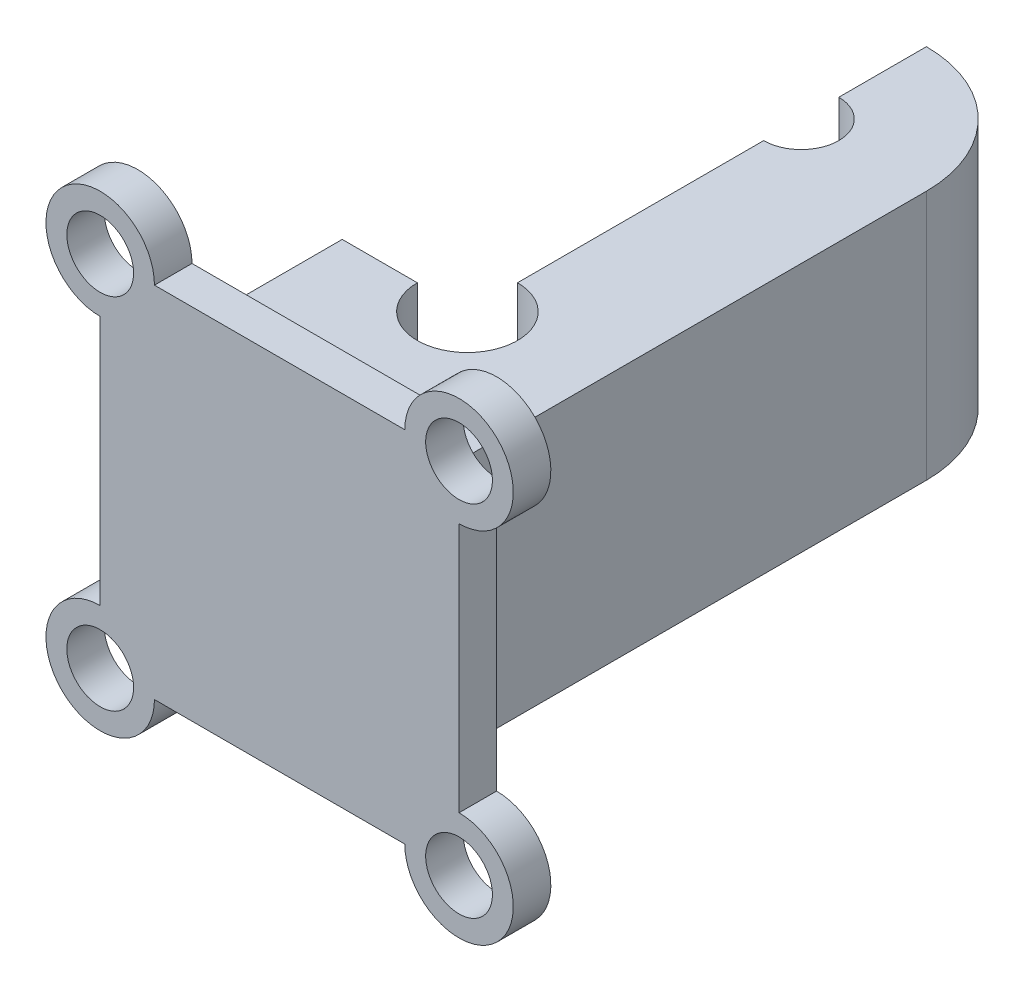
SolidWorks part; units mm, degrees
ref_plane "Ön Düzlem" through (0, 0, 0) normal (0, 0, 1) x (1, 0, 0)
ref_plane "Üst Düzlem" through (0, 0, 0) normal (0, 1, 0) x (1, 0, 0)
ref_plane "Sağ Düzlem" through (0, 0, 0) normal (1, 0, 0) x (0, 0, -1)
sketch "Çizim1" plane through (0, 0, 0) normal (0, 0, 1) x (1, 0, 0)
  line L5 (27.3051, -33.7264) -> (87.3051, -33.7264)
  line L10 (14.3051, -20.7264) -> (14.3051, 39.2736)
  line L12 (100.3051, 39.2736) -> (100.3051, -20.7264)
  line L13 (87.3051, 52.2736) -> (27.3051, 52.2736)
  circle A8 centre (14.3051, -33.7264) radius 13
  circle A10 centre (14.3051, -33.7264) radius 8
  circle A11 centre (100.3051, -33.7264) radius 8
  circle A12 centre (100.3051, -33.7264) radius 13
  circle A13 centre (14.3051, 52.2736) radius 8
  circle A14 centre (14.3051, 52.2736) radius 13
  circle A15 centre (100.3051, 52.2736) radius 8
  circle A16 centre (100.3051, 52.2736) radius 13
  dimension "D1" = 26
  dimension "D2" = 16
extrude "Yükseklik-Ekstrüzyon2" add sketch "Çizim1" along normal blind 9 contours A8 A10 | L12 A16 L13 A14 L10 A8 L5 A12 | A12 A11 | A16 A15 | A14 A13
sketch "Çizim2" plane through (0, 0, 0) normal (0, 0, -1) x (-1, 0, 0)
  line L0 (-57.3051, -33.7264) -> (-57.3051, 52.2736) construction
  line L1 (-27.3051, -33.7264) -> (-87.3051, -33.7264) construction
  line L2 (-87.3051, 52.2736) -> (-27.3051, 52.2736) construction
  line L4 (-87.3051, 39.2736) -> (-27.3051, 39.2736)
  line L5 (-87.3051, 39.2736) -> (-87.3051, -20.7264)
  line L6 (-87.3051, -20.7264) -> (-27.3051, -20.7264)
  line L7 (-27.3051, 39.2736) -> (-27.3051, -20.7264)
  line L8 (-87.3051, 39.2736) -> (-27.3051, -20.7264) construction
  line L9 (-87.3051, -20.7264) -> (-27.3051, 39.2736) construction
  point P6 (-57.3051, 9.2736)
  dimension "D1" = 60
  dimension "D2" = 60
extrude "Yükseklik-Ekstrüzyon3" add sketch "Çizim2" along normal blind 116
sketch "Çizim3" plane through (0, -20.7264, 0) normal (0, -1, 0) x (1, 0, 0)
  line L0 (57.3051, 0) -> (57.3051, -36) construction
  line L1 (27.3051, 0) -> (87.3051, 0) construction
  line L2 (57.3051, -48) -> (57.3051, -116)
  line L3 (87.3051, -116) -> (27.3051, -116) construction
  circle A0 centre (57.3051, -36) radius 12
  circle A1 centre (57.3051, -116) radius 30
  circle A2 centre (57.3051, -116) radius 10
  line M4 (27.3051, -116) -> (87.3051, -116)
  dimension "D2" = 24
  dimension "D3" = 60
  dimension "D4" = 20
  dimension "D1" = 36
extrude "Yükseklik-Ekstrüzyon4" add sketch "Çizim3" against normal blind 60 contours A2 A1 M4
sketch "Çizim4" plane through (0, -20.7264, 0) normal (0, -1, 0) x (1, 0, 0)
  line L1 (67.3051, -116) -> (47.3051, -116) construction
  circle A1 centre (57.3051, -116) radius 20
  dimension "D1" = 40
extrude "Kes-Ekstrüzyon2" cut sketch "Çizim4" against normal blind 220
sketch "Çizim5" plane through (0, -20.7264, 0) normal (0, -1, 0) x (1, 0, 0)
  line L0 (57.3051, 0) -> (57.3051, -36) construction
  line L1 (87.3051, 0) -> (27.3051, 0) construction
  circle A0 centre (57.3051, -36) radius 12
  dimension "D2" = 24
  dimension "D1" = 36
extrude "Kes-Ekstrüzyon3" cut sketch "Çizim5" against normal blind 220
sketch "Çizim6" plane through (0, -20.7264, 0) normal (0, -1, 0) x (-1, 0, 0)
  line L0 (-57.3051, 146) -> (-57.3051, 36)
  line L1 (-57.3051, 36) -> (-27.3051, 36)
  line L2 (-27.3051, 116) -> (-27.3051, 0) construction
  line L3 (-27.3051, 36) -> (-27.3051, 116)
  arc A0 (-27.3051, 116) -> (-87.3051, 116) centre (-57.3051, 116) ccw construction
  arc A1 (-57.3051, 146) -> (-27.3051, 116) centre (-57.3051, 116) cw
  circle M1 centre (-57.3051, 36) radius 12
  circle M2 centre (-57.3051, 116) radius 20
  line M4 (-27.3051, 0) -> (-27.3051, 116)
  arc M5 (-27.3051, 116) -> (-87.3051, 116) centre (-57.3051, 116) ccw
extrude "Kes-Ekstrüzyon4" cut sketch "Çizim6" against normal blind 220 contours L1 L0 M1 M4 M5 M2
ref_plane "Düzlem1" through (0, -0.7264, 0) normal (0, -1, 0) x (-1, 0, 0)
sketch "Çizim7" plane through (0, -0.7264, 0) normal (0, -1, 0) x (-1, 0, 0)
  line L0 (-57.3051, 131.1753) -> (-57.3051, 135.9993)
  line L2 (-57.3051, 96.0007) -> (-57.3051, 100.8247)
  arc A0 (-57.3051, 131.1753) -> (-57.3051, 100.8247) centre (-57.3051, 116) ccw
  arc A1 (-57.3051, 135.9993) -> (-57.3051, 96.0007) centre (-57.3051, 116) ccw
extrude "Yükseklik-Ekstrüzyon6" add sketch "Çizim7" against normal blind 20 separate body
ref_plane "Düzlem2" through (0, 19.2736, 0) normal (0, -1, 0) x (-1, 0, 0)
sketch "Çizim10" plane through (0, 19.2736, 0) normal (0, -1, 0) x (-1, 0, 0)
  line L0 (-57.3051, 96) -> (-57.3051, 107)
  line L1 (-57.3051, 125) -> (-57.3051, 136)
  arc A0 (-57.3051, 136) -> (-57.3051, 96) centre (-57.3051, 116) ccw
  arc A1 (-57.3051, 125) -> (-57.3051, 107) centre (-57.3051, 116) ccw
  dimension "D1" = 40
  dimension "D2" = 18
extrude "Yükseklik-Ekstrüzyon7" add sketch "Çizim10" against normal blind 20
sketch "Çizim11" plane through (0, -0.7264, 0) normal (0, -1, 0) x (-1, 0, 0)
  line L0 (-57.3051, 43) -> (-57.3051, 48)
  line L1 (-50.3051, 36) -> (-45.3051, 36)
  arc A0 (-57.3051, 43) -> (-50.3051, 36) centre (-57.3051, 36) ccw
  arc A1 (-57.3051, 48) -> (-45.3051, 36) centre (-57.3051, 36) ccw
  dimension "D1" = 14
extrude "Yükseklik-Ekstrüzyon8" add sketch "Çizim11" against normal blind 20
sketch "Çizim12" plane through (0, 0, -36) normal (0, 0, -1) x (-1, 0, 0)
  line L0 (-27.3051, -20.7264) -> (-27.3051, -11.7264)
  line L1 (-27.3051, 39.2736) -> (-27.3051, -20.7264) construction
  line L2 (-27.3051, -11.7264) -> (-36.8892, -11.7264)
  line L3 (-27.3051, 39.2736) -> (-27.3051, 30.2736)
  line L5 (-27.3051, 30.2736) -> (-36.8892, 30.2736)
  line L6 (-27.3051, -20.7264) -> (-45.3051, -20.7264)
  line L7 (-45.3051, -20.7264) -> (-45.3051, -0.7264)
  line L8 (-45.3051, -0.7264) -> (-50.3051, -0.7264)
  line L9 (-45.3051, -0.7264) -> (-50.3051, -0.7264) construction
  line L10 (-50.3051, -0.7264) -> (-50.3051, 19.2736)
  line L11 (-50.3051, 19.2736) -> (-45.3051, 19.2736)
  line L12 (-45.3051, 19.2736) -> (-45.3051, 39.2736)
  line L13 (-45.3051, 39.2736) -> (-27.3051, 39.2736)
  line L14 (-36.8892, -11.7264) -> (-36.8892, 30.2736)
  line L15 (-27.3051, -11.7264) -> (-27.3051, 30.2736)
  line M5 (-27.3051, -20.7264) -> (-27.3051, 39.2736)
  dimension "D1" = 9
  dimension "D2" = 9
extrude "Kes-Ekstrüzyon5" cut sketch "Çizim12" against normal blind 37 contours L14 L2 L5 M5
sketch "Çizim13" plane through (36.8892, 0, 0) normal (-1, 0, 0) x (0, 0, 1)
  line L0 (1, -11.7264) -> (-26.9994, -11.7264)
  line L1 (1, -11.7264) -> (-36, -11.7264) construction
  line L2 (-26.9994, -11.7264) -> (-26.9994, 30.2736)
  line L3 (1, 30.2736) -> (-36, 30.2736) construction
  line L4 (-26.9994, 30.2736) -> (1, 30.2736)
  line L5 (1, 30.2736) -> (1, -11.7264)
extrude "Kes-Ekstrüzyon6" cut sketch "Çizim13" against normal blind 9
sketch "Çizim15" plane through (0, 30.2736, 0) normal (0, -1, 0) x (1, 0, 0)
  line L0 (45.8892, -26.9994) -> (36.8892, -36)
  arc A0 (36.8892, -36) -> (45.8892, -26.9994) centre (41.3892, -31.4997) cw
extrude "Yükseklik-Ekstrüzyon9" add sketch "Çizim15" along normal blind 44
